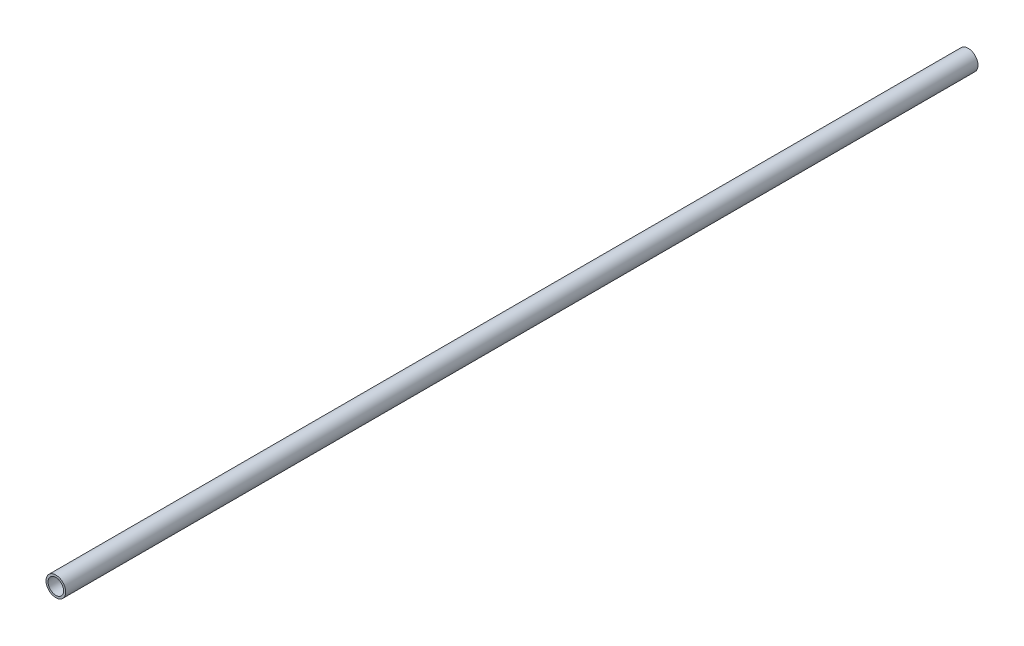
SolidWorks part; units mm, degrees
ref_plane "Front Plane" through (0, 0, 0) normal (0, 0, 1) x (1, 0, 0)
ref_plane "Top Plane" through (0, 0, 0) normal (0, 1, 0) x (1, 0, 0)
ref_plane "Right Plane" through (0, 0, 0) normal (1, 0, 0) x (0, 0, -1)
sketch "Sketch1" plane through (0, 0, 0) normal (0, 0, 1) x (1, 0, 0)
  circle A0 centre (0, 0) radius 12.065
  circle A1 centre (0, 0) radius 9.525
  dimension "D1" = 24.13
  dimension "D2" = 19.05
extrude "Boss-Extrude1" add sketch "Sketch1" along normal mid plane 1117.6
